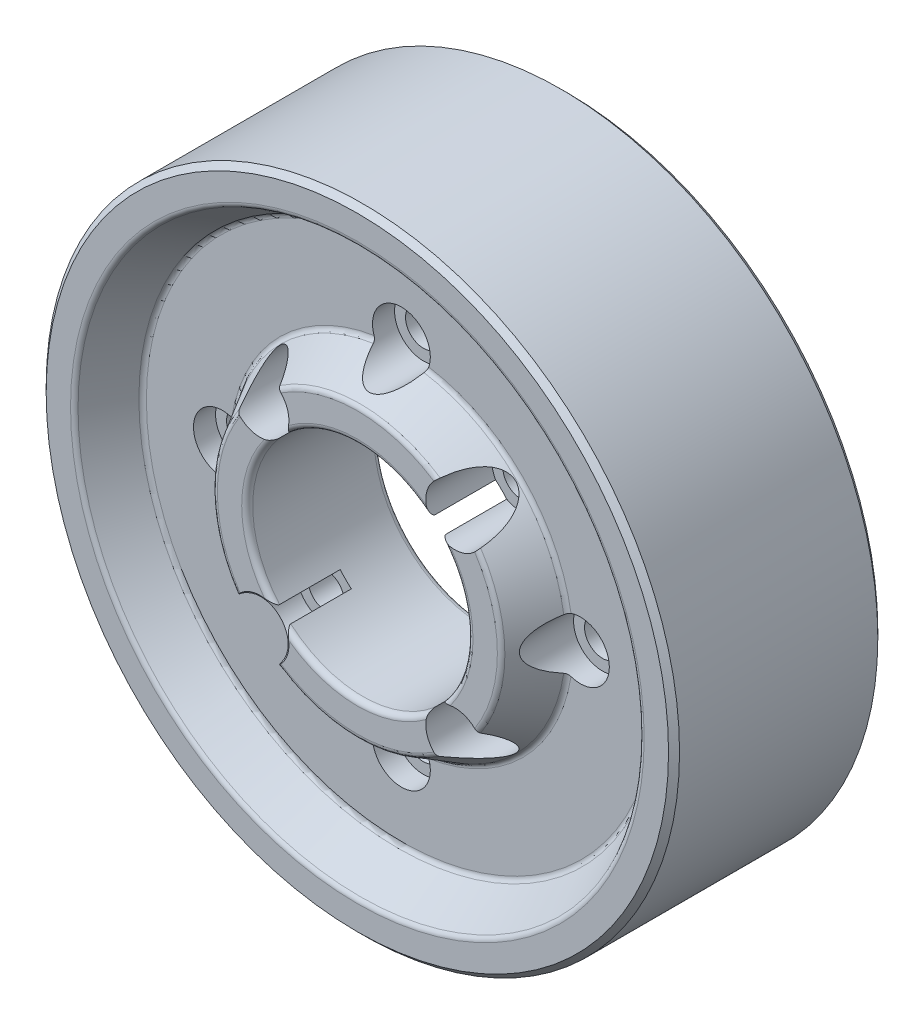
SolidWorks part; units mm, degrees
material "PE High Density"
ref_plane "Front Plane" through (0, 0, 0) normal (0, 0, 1) x (1, 0, 0)
ref_plane "Top Plane" through (0, 0, 0) normal (0, 1, 0) x (1, 0, 0)
ref_plane "Right Plane" through (0, 0, 0) normal (1, 0, 0) x (0, 0, -1)
sketch "Sketch1" plane through (0, 0, 0) normal (1, 0, 0) x (0, 0, -1)
  line L0 (-19, 20) -> (5, 20)
  line L1 (5, 20) -> (5, 37.5)
  line L2 (5, 37.5) -> (11, 37.5)
  line L3 (19, 51.5) -> (19, 57.5)
  line L4 (19, 57.5) -> (-19, 57.5)
  line L5 (-19, 57.5) -> (-19, 51.5)
  line L6 (-32.8, 0) -> (0, 0) construction
  line L7 (0, 0) -> (0, 57.5) construction
  line L8 (-19, 26) -> (-11, 30.6188)
  line L9 (-11, 30.6188) -> (-11, 46.8812)
  line L10 (-11, 46.8812) -> (-19, 51.5)
  line L11 (-19, 26) -> (-19, 20)
  line L12 (11, 37.5) -> (11, 46.8812)
  line L13 (11, 46.8812) -> (19, 51.5)
  dimension "D1" = 115
  dimension "D2" = 38
  dimension "D3" = 75
  dimension "D4" = 14
  dimension "D5" = 40
  dimension "D6" = 60
  dimension "D7" = 8
  dimension "D8" = 6
revolve "Revolve1" add sketch "Sketch1" angle 360 about L6
chamfer "Chamfer1" distance 1 angle 45 2 edges at (57.5, 0, -19) (57.5, 0, 19)
fillet "Fillet1" radius 1 10 edges at (46.8812, 0, 11) (30.6188, 0, 11) (51.5, 0, 19) (26, 0, 19) (20, 0, 19) (20, 0, -5) (37.5, 0, -5) (37.5, 0, -11) (46.8812, 0, -11) (51.5, 0, -19)
sketch "Sketch2" plane through (0, 0, 19) normal (0, 0, 1) x (1, 0, 0)
  line L0 (-17.6777, 17.6777) -> (17.6777, -17.6777) construction
  line L1 (17.6777, -17.6777) -> (-17.6777, -17.6777) construction
  circle A0 centre (0, 32.5) radius 3.25
  circle A1 centre (32.5, 0) radius 3.25
  circle A2 centre (17.6777, 17.6777) radius 3.25
  circle A3 centre (17.6777, -17.6777) radius 3.25
  circle A4 centre (0, -32.5) radius 3.25
  circle A5 centre (-17.6777, -17.6777) radius 3.25
  circle A6 centre (-32.5, 0) radius 3.25
  circle A7 centre (-17.6777, 17.6777) radius 3.25
  point P2 (0, 0)
  point P21 (0, 0)
  dimension "D2" = 6.5
  dimension "D3" = 65
  dimension "D4" = 50
  dimension "D1" = 4
extrude "Cut-Extrude1" cut sketch "Sketch2" against normal through all
sketch "Sketch3" plane through (0, 0, 19) normal (0, 0, 1) x (1, 0, 0)
  circle A0 centre (0, -32.5) radius 5.25
  circle A1 centre (0, -32.5) radius 3.25
  circle A2 centre (0, -32.5) radius 3.25
  circle A3 centre (17.6777, -17.6777) radius 3.25
  circle A4 centre (17.6777, -17.6777) radius 3.25
  circle A5 centre (17.6777, 17.6777) radius 3.25
  circle A6 centre (17.6777, 17.6777) radius 3.25
  circle A7 centre (32.5, 0) radius 3.25
  circle A8 centre (32.5, 0) radius 3.25
  circle A9 centre (0, 32.5) radius 3.25
  circle A10 centre (0, 32.5) radius 3.25
  circle A11 centre (-17.6777, 17.6777) radius 3.25
  circle A12 centre (-17.6777, 17.6777) radius 3.25
  circle A13 centre (-32.5, 0) radius 3.25
  circle A14 centre (-32.5, 0) radius 3.25
  circle A15 centre (-17.6777, -17.6777) radius 3.25
  circle A16 centre (-17.6777, -17.6777) radius 3.25
  circle A17 centre (17.6777, -17.6777) radius 5.25
  circle A18 centre (17.6777, 17.6777) radius 5.25
  circle A19 centre (32.5, 0) radius 5.25
  circle A20 centre (0, 32.5) radius 5.25
  circle A21 centre (-17.6777, 17.6777) radius 5.25
  circle A22 centre (-32.5, 0) radius 5.25
  circle A23 centre (-17.6777, -17.6777) radius 5.25
  dimension "D1" = 0
  dimension "D2" = 0
  dimension "D3" = 0
  dimension "D4" = 0
  dimension "D5" = 0
  dimension "D6" = 0
  dimension "D7" = 0
  dimension "D8" = 0
  dimension "D9" = 2
extrude "Cut-Extrude2" cut sketch "Sketch3" against normal blind 12
